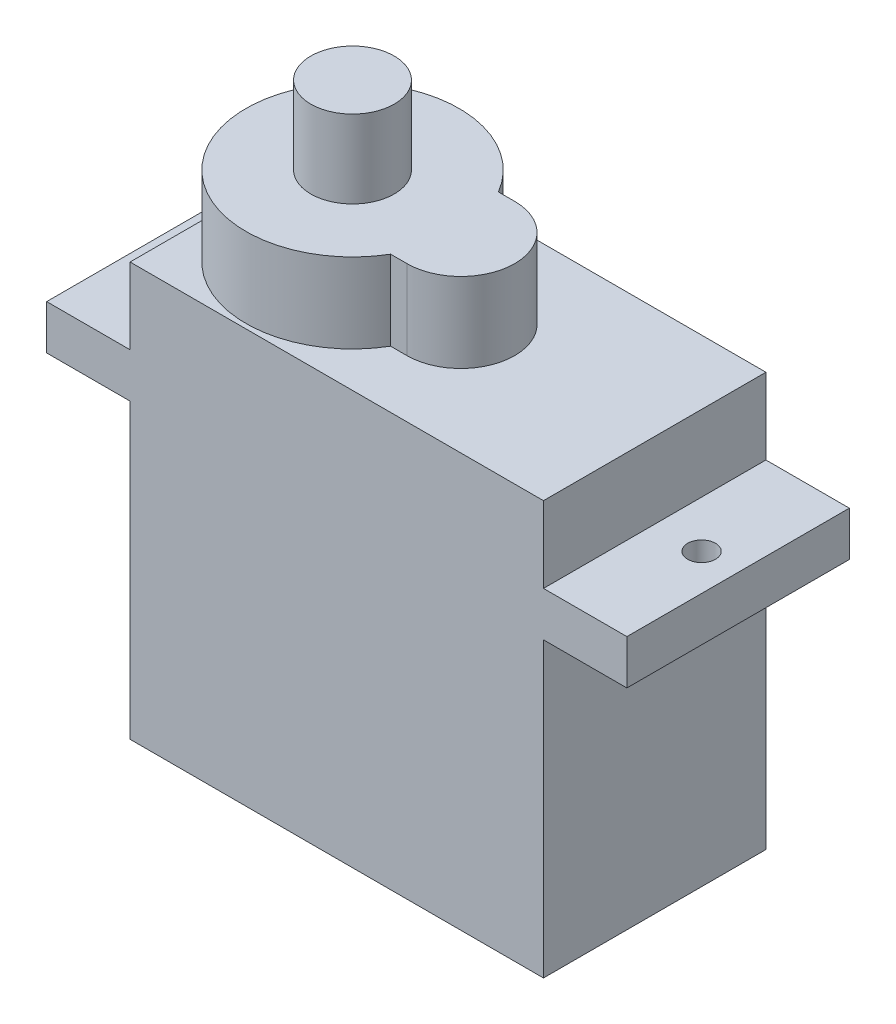
SolidWorks part; units mm, degrees
ref_plane "前视基准面" through (0, 0, 0) normal (0, 0, 1) x (1, 0, 0)
ref_plane "上视基准面" through (0, 0, 0) normal (0, 1, 0) x (1, 0, 0)
ref_plane "右视基准面" through (0, 0, 0) normal (1, 0, 0) x (0, 0, -1)
sketch "Sketch1" plane through (0, 0, 0) normal (0, 1, 0) x (1, 0, 0)
  line L1 (-11.15, 6) -> (11.15, 6)
  line L2 (-11.15, 6) -> (-11.15, -6)
  line L3 (-11.15, -6) -> (11.15, -6)
  line L4 (11.15, 6) -> (11.15, -6)
  line L5 (-11.15, 6) -> (11.15, -6) construction
  line L6 (-11.15, -6) -> (11.15, 6) construction
  point P4 (0, 0)
  dimension "D1" = 12
  dimension "D2" = 22.3
extrude "Boss-Extrude1" add sketch "Sketch1" along normal blind 22.3
sketch "Sketch2" plane through (-11.15, 0, 0) normal (-1, 0, 0) x (0, 0, 1)
  line L0 (-6, 22.3) -> (-6, 0) construction
  line L1 (-6, 18.2) -> (6, 18.2)
  line L2 (-6, 18.2) -> (-6, 15.8)
  line L3 (-6, 15.8) -> (6, 15.8)
  line L4 (6, 18.2) -> (6, 15.8)
  line L5 (-6, 18.2) -> (6, 15.8) construction
  line L6 (-6, 15.8) -> (6, 18.2) construction
  line L7 (6, 22.3) -> (6, 0) construction
  line L9 (-6, 22.3) -> (6, 22.3) construction
  point P4 (0, 17)
  dimension "D1" = 6.5
  dimension "D2" = 2.4
extrude "Boss-Extrude2" add sketch "Sketch2" along normal blind 4.5
sketch "Sketch5" plane through (0, 22.3, 0) normal (0, 1, 0) x (1, 0, 0)
  line L0 (0.3957, -2.9067) -> (50000.3957, -2.9067) construction
  line L1 (-11.15, 0) -> (11.15, 0) construction
  line L2 (0.6933, 2.9067) -> (-0.1888, 2.9067)
  line L3 (-0.1888, -2.9067) -> (0.6933, -2.9067)
  line L6 (11.15, -6) -> (11.15, 6) construction
  line L8 (-11.15, 6) -> (-11.15, -6) construction
  line L13 (-0.1222, 2.79) -> (-0.1222, -2.79) construction
  line L14 (-0.1888, 2.9067) -> (5.2347, 2.9067) construction
  circle A4 centre (-5.15, 0) radius 5.75 construction
  arc A6 (-0.1222, 2.79) -> (-0.1222, -2.79) centre (0.6933, 0) cw construction
  arc A7 (-0.1888, -2.9067) -> (-0.1888, 2.9067) centre (-5.15, 0) cw
  arc A8 (0.6933, -2.9067) -> (0.6933, 2.9067) centre (0.6933, 0) ccw
  point P3 (-11.15, 0)
  point P8 (3.6, 0)
  point P15 (0.6933, 2.9067)
  point P16 (0.6933, -2.9067)
  point P19 (-0.1888, 2.9067)
  point P20 (-0.1888, -2.9067)
  dimension "D1" = 11.5
  dimension "D2" = 6
  dimension "D4" = 5.58
  dimension "D3" = 8.75
mirror "镜向1" about plane through (0, 0, 0) normal (1, 0, 0) of "Boss-Extrude2"
extrude "凸台-拉伸1" add sketch "Sketch5" along normal blind 4.3
sketch "草图1" plane through (0, 18.2, 0) normal (0, 1, 0) x (1, 0, 0)
  line L0 (-13.68, 0) -> (13.68, 0) construction
  circle A0 centre (-13.68, 0) radius 0.75
  circle A1 centre (13.68, 0) radius 0.75
  point P4 (0, 0)
  dimension "D2" = 1.5
  dimension "D3" = 1.5
  dimension "D1" = 27.36
extrude "切除-拉伸1" cut sketch "草图1" against normal blind 10
sketch "草图2" plane through (0, 26.6, 0) normal (0, 1, 0) x (1, 0, 0)
  circle A0 centre (-5.15, 0) radius 2.25
  arc A1 (-0.1888, 2.9067) -> (-0.1888, -2.9067) centre (-5.15, 0) ccw construction
  dimension "D1" = 4.5
extrude "凸台-拉伸2" add sketch "草图2" along normal blind 4.2
